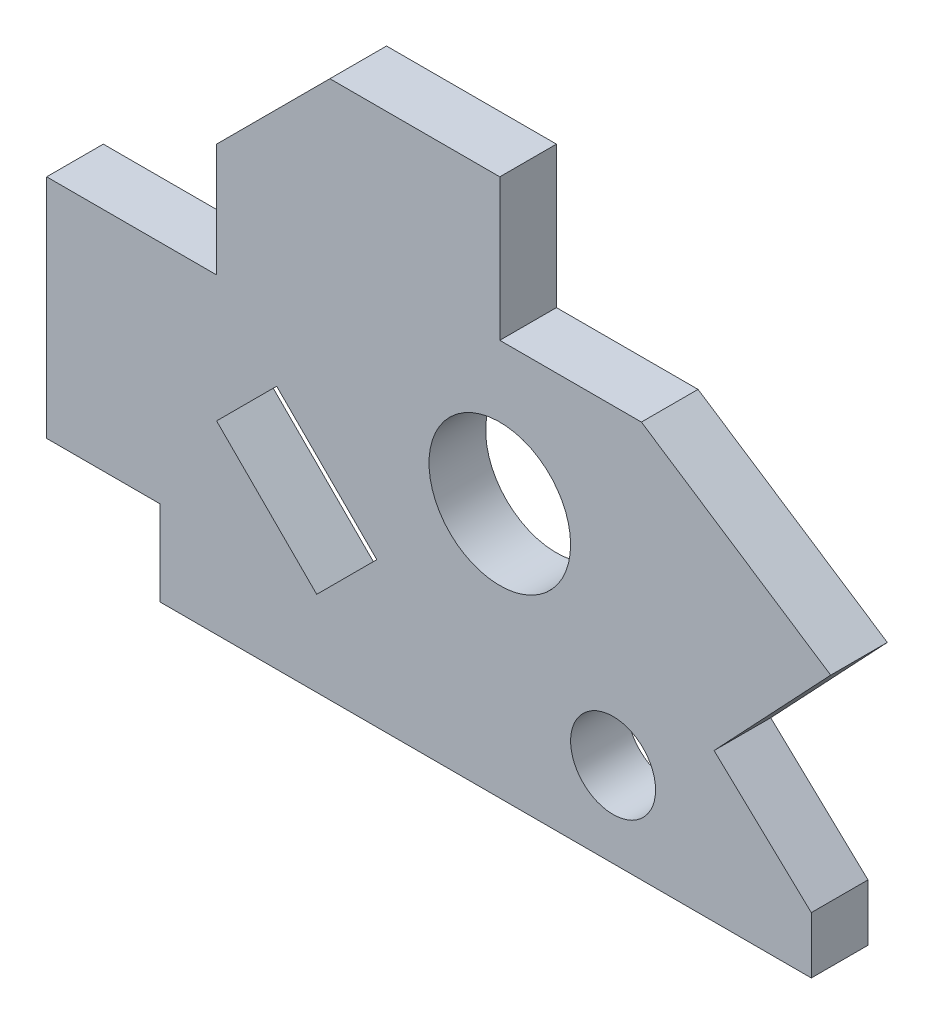
SolidWorks part; units mm, degrees
ref_plane "Alzado" through (0, 0, 0) normal (0, 0, 1) x (1, 0, 0)
ref_plane "Planta" through (0, 0, 0) normal (0, 1, 0) x (1, 0, 0)
ref_plane "Vista lateral" through (0, 0, 0) normal (1, 0, 0) x (0, 0, -1)
sketch "Croquis1" plane through (0, 0, 0) normal (0, 0, 1) x (1, 0, 0)
  line L0 (0, 0) -> (-115, 0)
  line L1 (-115, 0) -> (-115, 15)
  line L2 (-115, 15) -> (-135, 15)
  line L3 (-135, 15) -> (-135, 55)
  line L4 (-135, 55) -> (-105, 55)
  line L5 (-105, 55) -> (-105, 75)
  line L6 (-105, 75) -> (-85, 95)
  line L7 (-85, 95) -> (-55, 95)
  line L8 (-55, 95) -> (-55, 70)
  line L9 (-55, 70) -> (-30, 70)
  line L10 (-30, 70) -> (3.4191, 48.0191)
  line L11 (3.4191, 48.0191) -> (-17.1685, 26.1982)
  line L12 (-17.1685, 26.1982) -> (0, 10)
  line L13 (0, 10) -> (0, 0)
  line L14 (-105, 32.6777) -> (-87.3223, 15)
  line L15 (-87.3223, 15) -> (-76.7157, 25.6066)
  line L16 (-76.7157, 25.6066) -> (-94.3934, 43.2843)
  line L17 (-94.3934, 43.2843) -> (-105, 32.6777)
  circle A0 centre (-55, 45) radius 12.5
  circle A1 centre (-35, 15) radius 7.5
  dimension "D23" = 15
  dimension "D26" = 25
  dimension "D1" = 115
  dimension "D2" = 15
  dimension "D3" = 40
  dimension "D4" = 30
  dimension "D5" = 20
  dimension "D6" = 20
  dimension "D7" = 10
  dimension "D8" = 30
  dimension "D9" = 25
  dimension "D10" = 25
  dimension "D11" = 40
  dimension "D12" = 30
  dimension "D13" = 95
  dimension "D14" = 135
  dimension "D15" = 80
  dimension "D16" = 90
  dimension "D17" = 15
  dimension "D18" = 25
  dimension "D19" = 15
  dimension "D20" = 10
  dimension "D21" = 45
  dimension "D22" = 15
  dimension "D24" = 45
  dimension "D25" = 35
  dimension "D27" = 20
extrude "Saliente-Extruir1" add sketch "Croquis1" along normal blind 10
